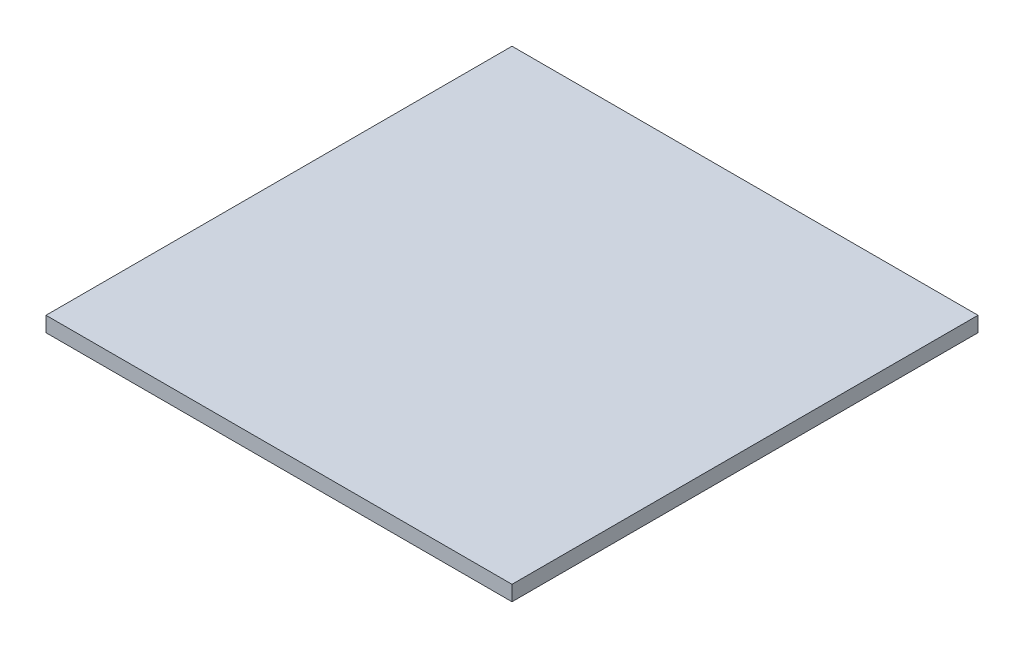
SolidWorks part; units mm, degrees
ref_plane "정면도" through (0, 0, 0) normal (0, 0, 1) x (1, 0, 0)
ref_plane "평면도" through (0, 0, 0) normal (0, 1, 0) x (1, 0, 0)
ref_plane "우측면도" through (0, 0, 0) normal (1, 0, 0) x (0, 0, -1)
sketch "스케치1" plane through (0, 0, 0) normal (0, 1, 0) x (1, 0, 0)
  line L1 (200, 200) -> (-200, 200)
  line L2 (200, 200) -> (200, -200)
  line L3 (200, -200) -> (-200, -200)
  line L4 (-200, 200) -> (-200, -200)
  line L5 (0, -200) -> (0, 200) construction
  line L6 (200, 0) -> (-200, 0) construction
  point P0 (0, 0)
  dimension "D1" = 400
  dimension "D2" = 400
extrude "보스-돌출1" add sketch "스케치1" along normal blind 13
